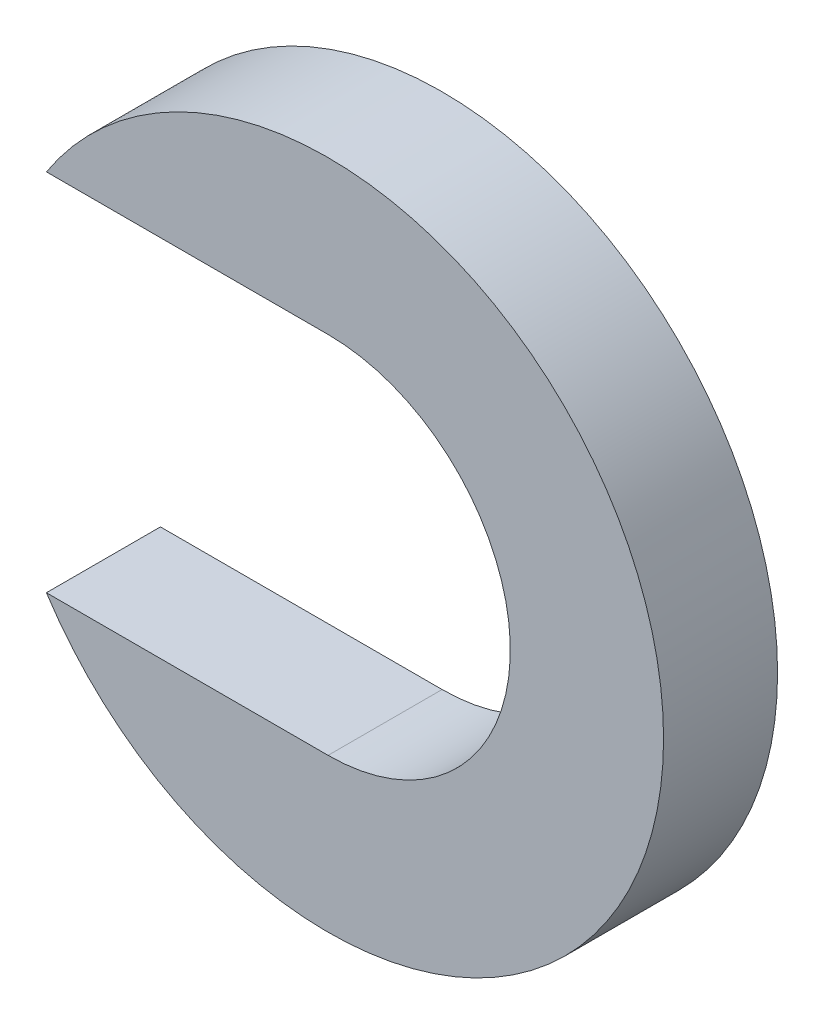
SolidWorks part; units mm, degrees
ref_plane "Front" through (0, 0, 0) normal (0, 0, 1) x (1, 0, 0)
ref_plane "Top" through (0, 0, 0) normal (0, 1, 0) x (1, 0, 0)
ref_plane "Right" through (0, 0, 0) normal (1, 0, 0) x (0, 0, -1)
sketch "Sketch1" plane through (0, 0, 0) normal (0, 0, 1) x (1, 0, 0)
  line L0 (15.9509, 0) -> (-15.9509, 0) construction
  line L1 (15.9509, 4.953) -> (-15.9509, 4.953) construction
  line L2 (15.9509, -4.953) -> (-15.9509, -4.953) construction
  line L3 (0, 4.953) -> (-7.6562, 4.953)
  line L4 (-7.6562, -4.953) -> (0, -4.953)
  arc A0 (-7.6562, -4.953) -> (-7.6562, 4.953) centre (0, 0) ccw
  arc A1 (0, -4.953) -> (0, 4.953) centre (0, 0) ccw
  point P5 (0, 0)
  dimension "D1" = 18.2372
  dimension "D2" = 4.953
  dimension "D3" = 4.953
extrude "Boss-Extrude1" add sketch "Sketch1" along normal blind 3.0988
